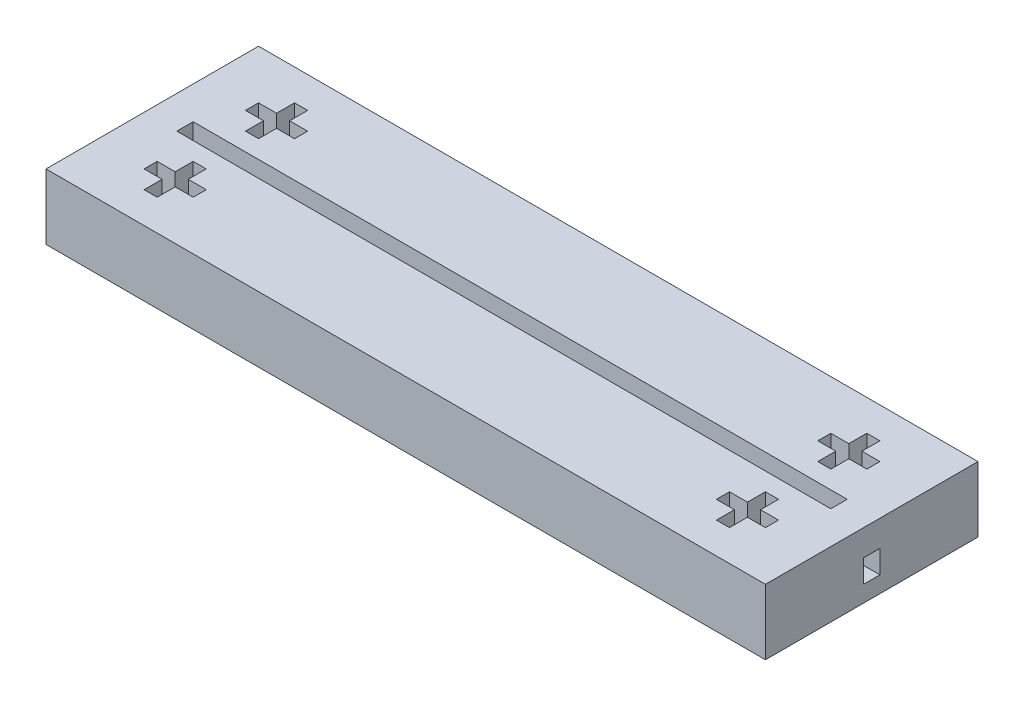
SolidWorks part; units mm, degrees
ref_plane "Přední rovina" through (0, 0, 0) normal (0, 0, 1) x (1, 0, 0)
ref_plane "Horní rovina" through (0, 0, 0) normal (0, 1, 0) x (1, 0, 0)
ref_plane "Pravá rovina" through (0, 0, 0) normal (1, 0, 0) x (0, 0, -1)
sketch "Skica1" plane through (0, 0, 0) normal (0, 1, 0) x (1, 0, 0)
  line L1 (0, 0) -> (220, 0)
  line L2 (0, 0) -> (0, 65)
  line L3 (0, 65) -> (220, 65)
  line L4 (220, 0) -> (220, 65)
  dimension "D1" = 65
  dimension "D2" = 220
extrude "Přidat vysunutím1" add sketch "Skica1" along normal blind 20
sketch "Skica2" plane through (0, 20, 0) normal (0, 1, 0) x (1, 0, 0)
  line L0 (0, 65) -> (0, 0) construction
  line L1 (10, 35) -> (210, 35)
  line L2 (10, 35) -> (10, 30)
  line L3 (10, 30) -> (210, 30)
  line L4 (210, 35) -> (210, 30)
  line L5 (220, 0) -> (220, 65) construction
  line L6 (220, 65) -> (0, 65) construction
  line L7 (0, 0) -> (220, 0) construction
  line L20 (24.5, 46) -> (30, 46)
  line L21 (20.5, 55.5) -> (24.5, 55.5)
  line L22 (20.5, 55.5) -> (20.5, 50)
  line L23 (20.5, 40.5) -> (24.5, 40.5)
  line L24 (24.5, 55.5) -> (24.5, 50)
  line L25 (15, 50) -> (20.5, 50)
  line L26 (15, 50) -> (15, 46)
  line L27 (15, 46) -> (20.5, 46)
  line L28 (30, 50) -> (30, 46)
  line L29 (20.5, 46) -> (20.5, 40.5)
  line L30 (24.5, 46) -> (24.5, 40.5)
  line L31 (24.5, 50) -> (30, 50)
  line L32 (0, 32.5) -> (220, 32.5) construction
  line L33 (0, 0) -> (220, 0)
  line L34 (0, 0) -> (0, 65)
  line L35 (0, 65) -> (220, 65)
  line L36 (220, 0) -> (220, 65) construction
  line L37 (15, 15) -> (15, 19)
  line L38 (110, 65) -> (110, 0) construction
  line L39 (15, 19) -> (20.5, 19)
  line L40 (20.5, 19) -> (20.5, 24.5)
  line L41 (20.5, 24.5) -> (24.5, 24.5)
  line L42 (24.5, 19) -> (24.5, 24.5)
  line L43 (24.5, 19) -> (30, 19)
  line L44 (30, 15) -> (30, 19)
  line L45 (24.5, 15) -> (30, 15)
  line L46 (24.5, 9.5) -> (24.5, 15)
  line L47 (20.5, 9.5) -> (24.5, 9.5)
  line L48 (20.5, 9.5) -> (20.5, 15)
  line L49 (15, 15) -> (20.5, 15)
  line L50 (205, 15) -> (199.5, 15)
  line L51 (199.5, 9.5) -> (199.5, 15)
  line L52 (199.5, 9.5) -> (195.5, 9.5)
  line L53 (195.5, 9.5) -> (195.5, 15)
  line L54 (195.5, 15) -> (190, 15)
  line L55 (190, 15) -> (190, 19)
  line L56 (195.5, 19) -> (190, 19)
  line L57 (195.5, 19) -> (195.5, 24.5)
  line L58 (199.5, 24.5) -> (195.5, 24.5)
  line L59 (199.5, 19) -> (199.5, 24.5)
  line L60 (205, 19) -> (199.5, 19)
  line L61 (205, 15) -> (205, 19)
  line L62 (205, 50) -> (205, 46)
  line L63 (205, 46) -> (199.5, 46)
  line L64 (199.5, 46) -> (199.5, 40.5)
  line L65 (199.5, 40.5) -> (195.5, 40.5)
  line L66 (195.5, 46) -> (195.5, 40.5)
  line L67 (195.5, 46) -> (190, 46)
  line L68 (190, 50) -> (190, 46)
  line L69 (195.5, 50) -> (190, 50)
  line L70 (195.5, 55.5) -> (195.5, 50)
  line L71 (199.5, 55.5) -> (195.5, 55.5)
  line L72 (199.5, 55.5) -> (199.5, 50)
  line L73 (205, 50) -> (199.5, 50)
  dimension "D1" = 10
  dimension "D2" = 10
  dimension "D3" = 30
  dimension "D4" = 30
  dimension "D5" = 4
  dimension "D6" = 15
  dimension "D7" = 15
  dimension "D8" = 15
extrude "Odebrat vysunutím1" cut sketch "Skica2" against normal blind 15 contours L4 L1 L2 L3 | L31 L24 L21 L22 L25 L26 L27 L29 L23 L30 L20 L28 | L37 L49 L48 L47 L46 L45 L44 L43 L42 L41 L40 L39 | L50 L61 L60 L59 L58 L57 L56 L55 L54 L53 L52 L51 | L62 L73 L72 L71 L70 L69 L68 L67 L66 L65 L64 L63
sketch "Skica3" plane through (220, 0, 0) normal (1, 0, 0) x (0, 0, -1)
  line L0 (0, 20) -> (0, 0) construction
  line L1 (30, 5) -> (35, 5)
  line L2 (30, 5) -> (30, 12)
  line L3 (30, 12) -> (35, 12)
  line L4 (35, 5) -> (35, 12)
  line L5 (65, 20) -> (65, 0) construction
  line L6 (0, 0) -> (65, 0) construction
  dimension "D1" = 30
  dimension "D2" = 30
  dimension "D3" = 5
  dimension "D4" = 7
extrude "Odebrat vysunutím2" cut sketch "Skica3" against normal blind 35
